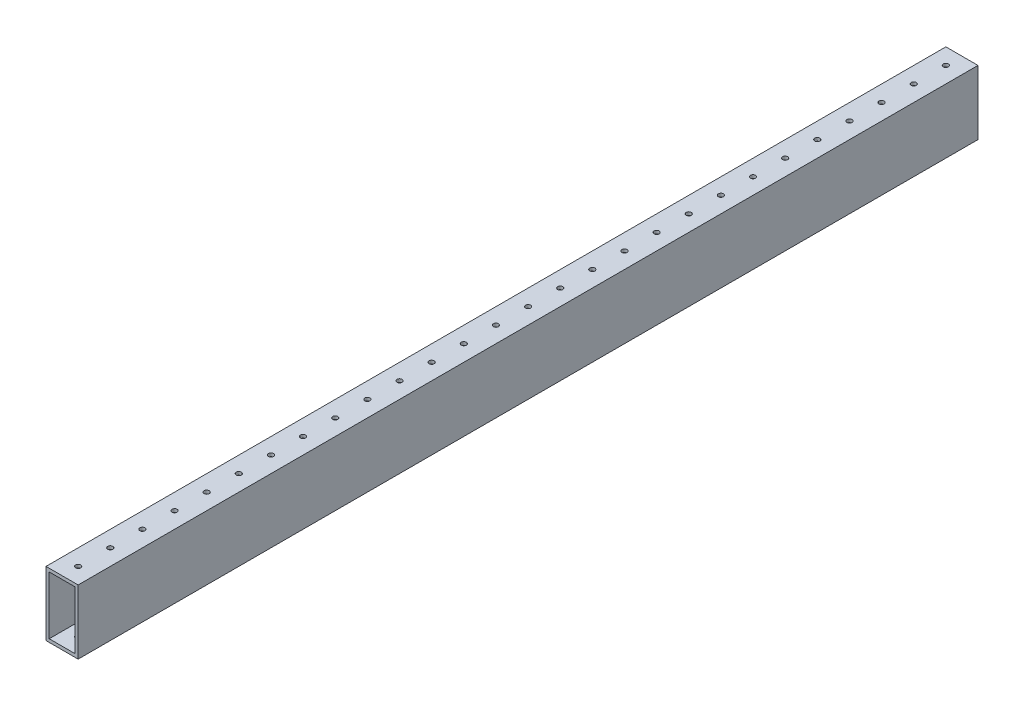
SolidWorks part; units mm, degrees
ref_plane "Front Plane" through (0, 0, 0) normal (0, 0, 1) x (1, 0, 0)
ref_plane "Top Plane" through (0, 0, 0) normal (0, 1, 0) x (1, 0, 0)
ref_plane "Right Plane" through (0, 0, 0) normal (1, 0, 0) x (0, 0, -1)
sketch "Sketch1" plane through (0, 0, 0) normal (0, 0, 1) x (1, 0, 0)
  line L0 (-10.16, 22.86) -> (10.16, 22.86)
  line L1 (-12.7, 25.4) -> (12.7, 25.4)
  line L2 (-12.7, 25.4) -> (-12.7, -25.4)
  line L3 (-12.7, -25.4) -> (12.7, -25.4)
  line L4 (12.7, 25.4) -> (12.7, -25.4)
  line L5 (-12.7, 25.4) -> (12.7, -25.4) construction
  line L6 (-12.7, -25.4) -> (12.7, 25.4) construction
  line L7 (10.16, 22.86) -> (10.16, -22.86)
  line L8 (-10.16, -22.86) -> (10.16, -22.86)
  line L9 (-10.16, 22.86) -> (-10.16, -22.86)
  point P0 (0, 0)
  dimension "D1" = 50.8
  dimension "D2" = 25.4
  dimension "D3" = 2.54
extrude "Boss-Extrude1" add sketch "Sketch1" against normal blind 711.2
sketch "Sketch2" plane through (0, 25.4, 0) normal (0, 1, 0) x (1, 0, 0)
  line L0 (0, -1000) -> (0, 49000) construction
  line L1 (12.7, 0) -> (-12.7, 0) construction
  line L2 (0, 12.7) -> (0, 38.1) construction
  circle A0 centre (0, 12.7) radius 2.032
  circle A1 centre (0, 38.1) radius 2.032
  circle A2 centre (0, 63.5) radius 2.032
  circle A3 centre (0, 88.9) radius 2.032
  circle A4 centre (0, 114.3) radius 2.032
  circle A5 centre (0, 139.7) radius 2.032
  circle A6 centre (0, 165.1) radius 2.032
  circle A7 centre (0, 190.5) radius 2.032
  circle A8 centre (0, 215.9) radius 2.032
  circle A9 centre (0, 241.3) radius 2.032
  circle A10 centre (0, 266.7) radius 2.032
  circle A11 centre (0, 292.1) radius 2.032
  circle A12 centre (0, 317.5) radius 2.032
  circle A13 centre (0, 342.9) radius 2.032
  circle A14 centre (0, 368.3) radius 2.032
  circle A15 centre (0, 393.7) radius 2.032
  circle A16 centre (0, 419.1) radius 2.032
  circle A17 centre (0, 444.5) radius 2.032
  circle A18 centre (0, 469.9) radius 2.032
  circle A19 centre (0, 495.3) radius 2.032
  circle A20 centre (0, 520.7) radius 2.032
  circle A21 centre (0, 546.1) radius 2.032
  circle A22 centre (0, 571.5) radius 2.032
  circle A23 centre (0, 596.9) radius 2.032
  circle A24 centre (0, 622.3) radius 2.032
  circle A25 centre (0, 647.7) radius 2.032
  circle A26 centre (0, 673.1) radius 2.032
  circle A27 centre (0, 698.5) radius 2.032
  circle A28 centre (0, 723.9) radius 2.032
  circle A29 centre (0, 749.3) radius 2.032
  dimension "D1" = 4.064
  dimension "D2" = 12.7
  dimension "D4" = 25.4
  dimension "D3" = 30
extrude "Cut-Extrude1" cut sketch "Sketch2" against normal through all
